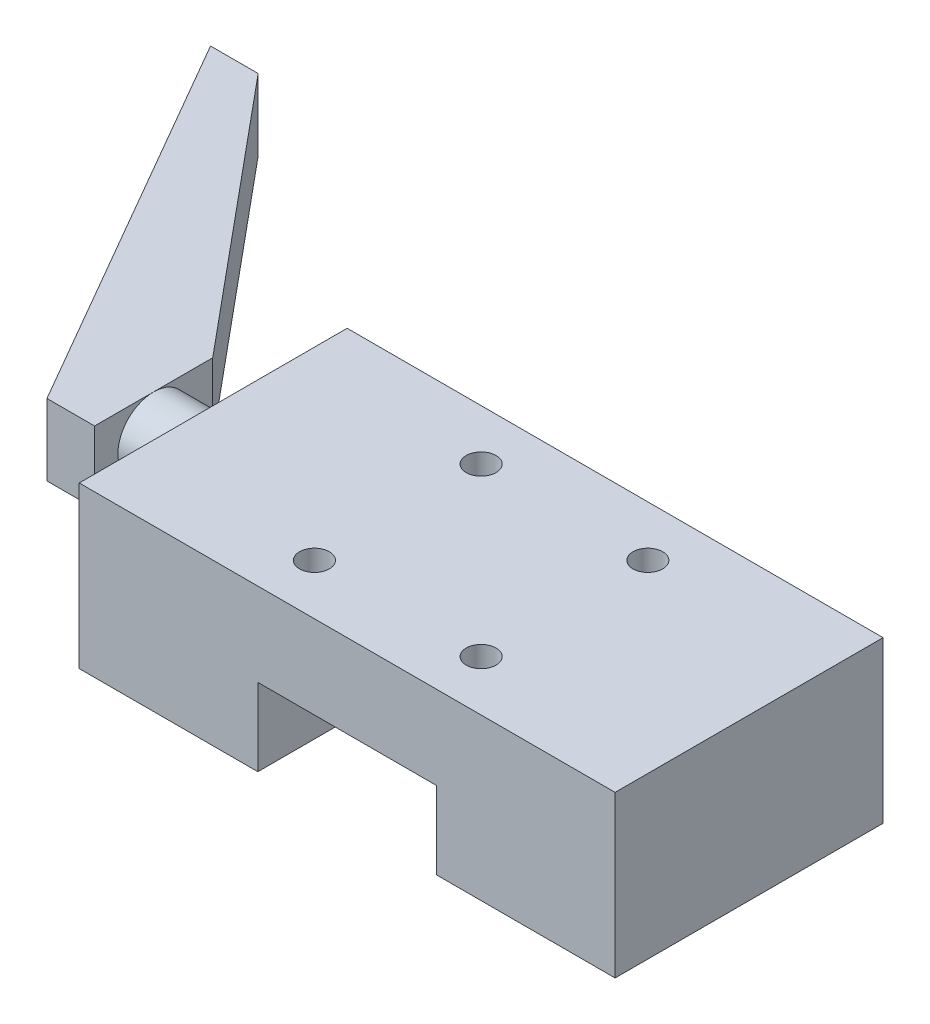
SolidWorks part; units mm, degrees
ref_plane "前视基准面" through (0, 0, 0) normal (0, 0, 1) x (1, 0, 0)
ref_plane "上视基准面" through (0, 0, 0) normal (0, 1, 0) x (1, 0, 0)
ref_plane "右视基准面" through (0, 0, 0) normal (1, 0, 0) x (0, 0, -1)
sketch "草图1" plane through (0, 0, 0) normal (0, 0, 1) x (1, 0, 0)
  line L1 (-45, 13.5) -> (45, 13.5)
  line L2 (-45, 13.5) -> (-45, -13.5)
  line L3 (-45, -13.5) -> (45, -13.5)
  line L4 (45, 13.5) -> (45, -13.5)
  line L5 (-45, 13.5) -> (45, -13.5) construction
  line L6 (-45, -13.5) -> (45, 13.5) construction
  point P0 (0, 0)
  dimension "D1" = 27
  dimension "D2" = 90
extrude "凸台-拉伸1" add sketch "草图1" along normal blind 45
sketch "草图2" plane through (0, 0, 45) normal (0, 0, 1) x (1, 0, 0)
  line L0 (-45, -13.5) -> (45, -13.5) construction
  line L1 (-15, -0.5) -> (15, -0.5)
  line L2 (-15, -0.5) -> (-15, -26.5)
  line L3 (-15, -26.5) -> (15, -26.5)
  line L4 (15, -0.5) -> (15, -26.5)
  line L5 (-15, -0.5) -> (15, -26.5) construction
  line L6 (-15, -26.5) -> (15, -0.5) construction
  point P0 (0, -13.5)
  dimension "D1" = 30
  dimension "D2" = 13
extrude "切除-拉伸1" cut sketch "草图2" against normal through all
sketch "草图3" plane through (0, 13.5, 0) normal (0, 1, 0) x (1, 0, 0)
  line L0 (0, 0) -> (0, -45) construction
  line L1 (45, -45) -> (-45, -45) construction
  line L3 (-14, -36.5) -> (14, -36.5) construction
  line L4 (-14, -36.5) -> (-14, -8.5) construction
  line L5 (-14, -8.5) -> (14, -8.5) construction
  line L6 (14, -36.5) -> (14, -8.5) construction
  line L7 (-14, -36.5) -> (14, -8.5) construction
  line L8 (-14, -8.5) -> (14, -36.5) construction
  point P5 (0, -22.5)
  dimension "D1" = 28
hole_wizard "M6 螺纹孔1" positions "草图4" profile "草图5" tap size "M6" standard "GB"
sketch "草图4" plane through (0, 13.5, 0) normal (0, 1, 0) x (1, 0, 0)
  point P0 (-14, -8.5)
  point P3 (14, -8.5)
  point P6 (14, -36.5)
  point P9 (-14, -36.5)
sketch "草图5" plane through (-14, 13.5, 8.5) normal (1, 0, 0) x (0, 0, 1)
  line L0 (0, 0) -> (0, 12.5022)
  line L1 (0, 12.5022) -> (2.5, 11)
  line L2 (2.5, 11) -> (2.5, 0)
  line L5 (2.5, 0) -> (0, 0)
  line L10 (0, 12.5022) -> (-2.5, 11) construction
  line L11 (0, -6.35) -> (0, 107.95) construction
  dimension "螺纹孔钻头直径" = 5
  dimension "螺纹孔钻头深度" = 11
  dimension "导头角度" = 118
cosmetic thread "孔螺蚊线1" parameters "D1"=8, "D2"=6
cosmetic thread "孔螺蚊线2" parameters "D1"=8, "D2"=6
cosmetic thread "孔螺蚊线3" parameters "D1"=8, "D2"=6
cosmetic thread "孔螺蚊线4" parameters "D1"=8, "D2"=6
sketch "草图6" plane through (-45, 0, 0) normal (-1, 0, 0) x (0, 0, 1)
  line L0 (22.5, 13.5) -> (22.5, 4.5) construction
  line L1 (45, 13.5) -> (0, 13.5) construction
  circle A0 centre (22.5, 4.5) radius 6
  dimension "D2" = 12
  dimension "D1" = 9
extrude "凸台-拉伸2" add sketch "草图6" along normal blind 10
ref_plane "基准面1" through (0, 4.5, 0) normal (0, 1, 0) x (1, 0, 0)
sketch "草图8" plane through (0, 4.5, 0) normal (0, 1, 0) x (1, 0, 0)
  line L0 (-55, -32.4202) -> (-55, -12.5798)
  line L1 (-55, -16.5) -> (-55, -28.5) construction
  line L2 (-55, -32.4202) -> (-63, -32.4202)
  line L3 (-63, -32.4202) -> (-100.5278, 32.5798)
  line L4 (-100.5278, 32.5798) -> (-92.5278, 32.5798)
  line L5 (-92.5278, 32.5798) -> (-55, -12.5798)
  point P0 (-92.4566, 31.7071)
  point P3 (-55, -22.5)
  dimension "D1" = 8
  dimension "D2" = 30
  dimension "D3" = 65
extrude "凸台-拉伸3" add sketch "草图8" along normal mid plane 12
